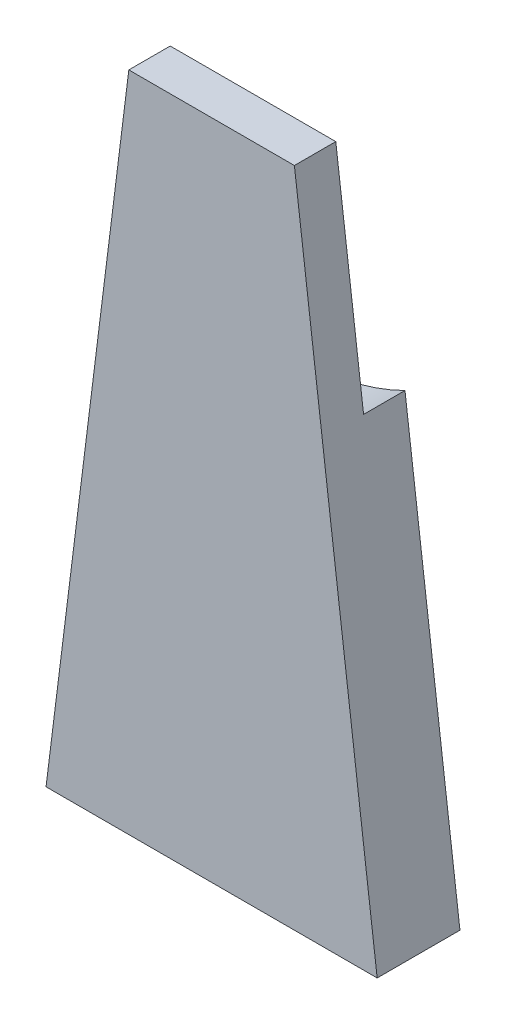
SolidWorks part; units mm, degrees
ref_plane "Front Plane" through (0, 0, 0) normal (0, 0, 1) x (1, 0, 0)
ref_plane "Top Plane" through (0, 0, 0) normal (0, 1, 0) x (1, 0, 0)
ref_plane "Right Plane" through (0, 0, 0) normal (1, 0, 0) x (0, 0, -1)
sketch "Sketch1" plane through (0, 0, 0) normal (0, 0, 1) x (1, 0, 0)
  line L0 (-10, 0) -> (10, 0)
  line L1 (10, 0) -> (20, -80)
  line L2 (20, -80) -> (-20, -80)
  line L3 (0, 0) -> (0, -80) construction
  line L4 (-10, 0) -> (-20, -80)
  dimension "D1" = 80
  dimension "D2" = 10
  dimension "D3" = 20
extrude "Boss-Extrude1" add sketch "Sketch1" along normal blind 5
sketch "Sketch2" plane through (0, 0, 0) normal (0, 0, 1) x (1, 0, 0)
  line L0 (10, 0) -> (-10, 0) construction
  line L5 (20, -80) -> (10, 0)
  line L6 (-20, -80) -> (20, -80)
  line L7 (-10, 0) -> (-20, -80)
  line L8 (10, 0) -> (-10, 0)
  line L9 (20, -80) -> (13.3578, -26.8621)
  line L10 (-20, -80) -> (20, -80)
  line L11 (-13.3578, -26.8621) -> (-20, -80)
  arc A0 (-13.3578, -26.8621) -> (13.3578, -26.8621) centre (0, 0) ccw
  dimension "D2" = 30
  dimension "D1" = 0
extrude "Boss-Extrude2" add sketch "Sketch2" against normal blind 5
